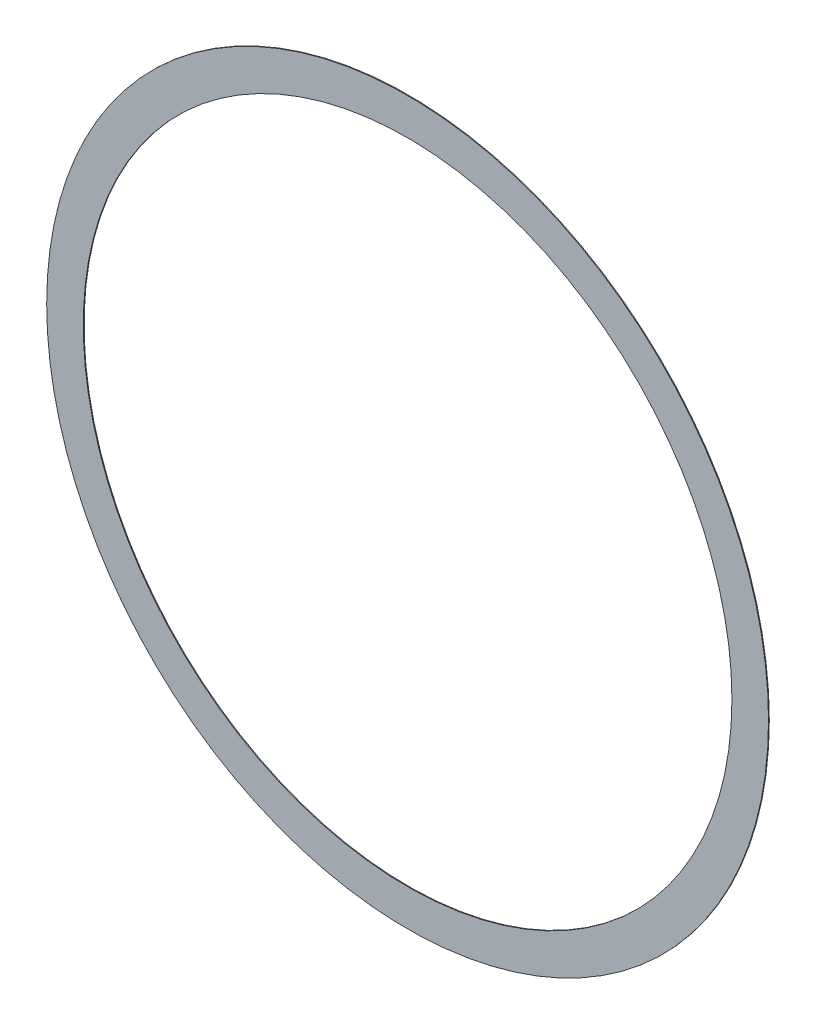
SolidWorks part; units mm, degrees
material "M/S SHIM"
ref_plane "Front Plane" through (0, 0, 0) normal (0, 0, 1) x (1, 0, 0)
ref_plane "Top Plane" through (0, 0, 0) normal (0, 1, 0) x (1, 0, 0)
ref_plane "Right Plane" through (0, 0, 0) normal (1, 0, 0) x (0, 0, -1)
sketch "Sketch1" plane through (0, 0, 0) normal (0, 0, 1) x (1, 0, 0)
  circle A0 centre (0, 0) radius 69
  circle A1 centre (0, 0) radius 62
  dimension "D1" = 138
  dimension "D2" = 124
extrude "Boss-Extrude1" add sketch "Sketch1" along normal blind 0.15
